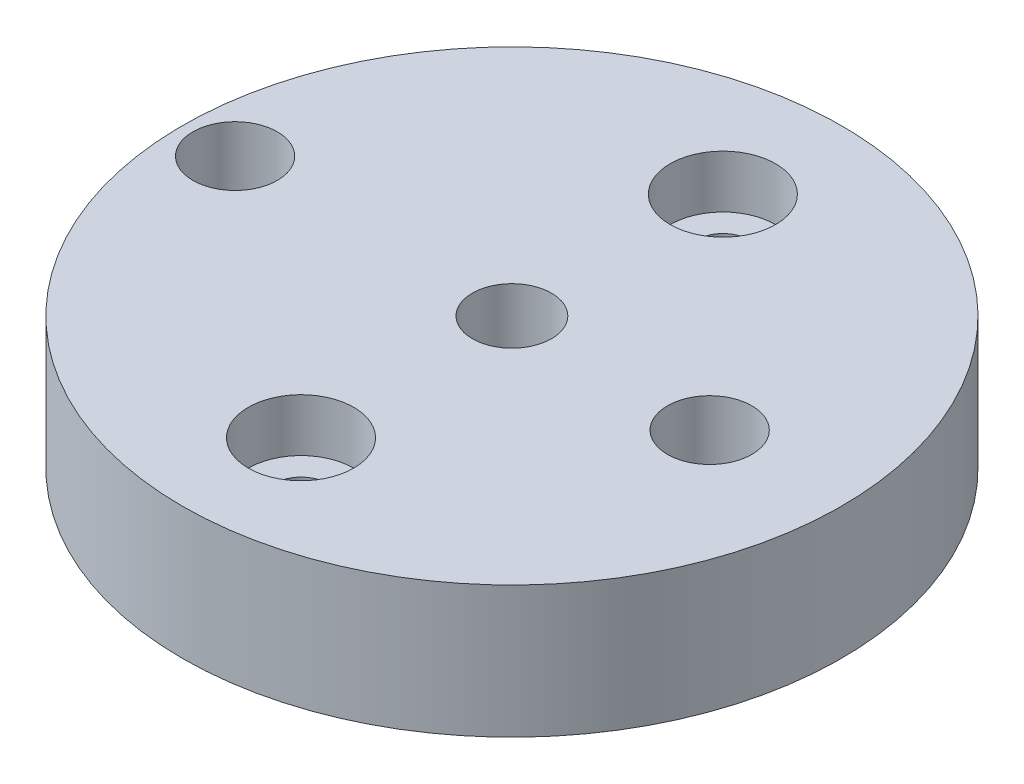
SolidWorks part; units mm, degrees
ref_plane "Front Plane" through (0, 0, 0) normal (0, 0, 1) x (1, 0, 0)
ref_plane "Top Plane" through (0, 0, 0) normal (0, 1, 0) x (1, 0, 0)
ref_plane "Right Plane" through (0, 0, 0) normal (1, 0, 0) x (0, 0, -1)
sketch "Sketch1" plane through (0, 0, 0) normal (0, 1, 0) x (1, 0, 0)
  line L0 (0, 0) -> (0, -8) construction
  circle A0 centre (0, 0) radius 12.5
  circle A1 centre (0, -8) radius 1
  circle A2 centre (-8, 0) radius 1 construction
  circle A3 centre (0, 8) radius 1
  circle A4 centre (8, 0) radius 1 construction
  circle A5 centre (0, 0) radius 1.5
  circle A6 centre (-10.5, 0) radius 1.6
  circle A7 centre (7.5, 0) radius 1.6
  circle A8 centre (0, 0) radius 5.75 construction
  dimension "D1" = 25
  dimension "D2" = 2
  dimension "D3" = 3
  dimension "D6" = 3.2
  dimension "D7" = 3.2
  dimension "D9" = 10.5
  dimension "D10" = 11.5
  dimension "D5" = 8
  dimension "D8" = 18
  dimension "D4" = 4
extrude "Boss-Extrude1" add sketch "Sketch1" along normal blind 5
sketch "Sketch2" plane through (0, 5, 0) normal (0, 1, 0) x (1, 0, 0)
  circle A0 centre (0, 8) radius 2
  circle A1 centre (0, -8) radius 2
  dimension "D1" = 4
extrude "Cut-Extrude1" cut sketch "Sketch2" against normal blind 2
